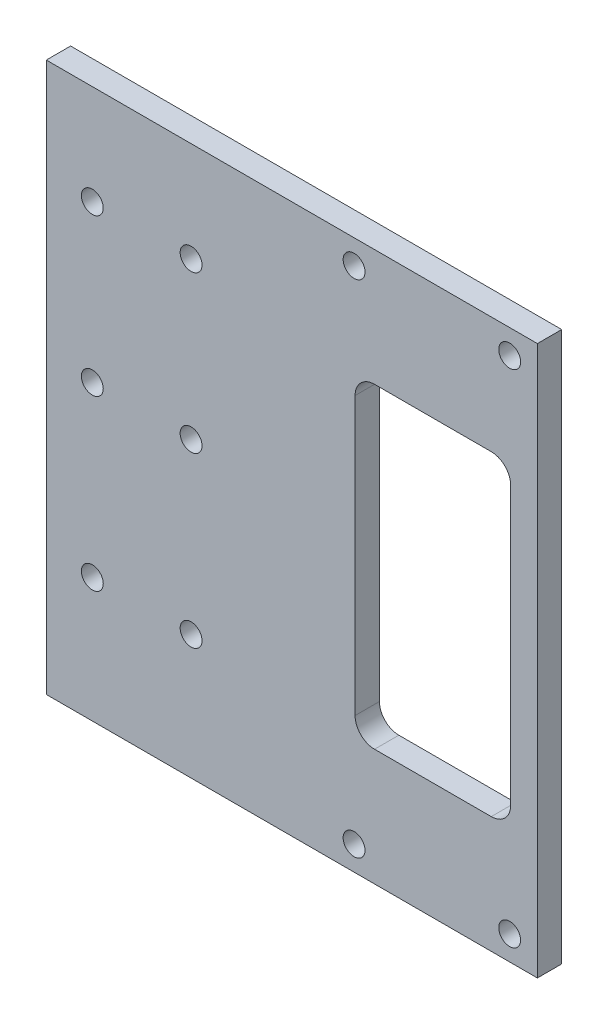
SolidWorks part; units mm, degrees
ref_plane "Plan de face" through (0, 0, 0) normal (0, 0, 1) x (1, 0, 0)
ref_plane "Plan de dessus" through (0, 0, 0) normal (0, 1, 0) x (1, 0, 0)
ref_plane "Plan de droite" through (0, 0, 0) normal (1, 0, 0) x (0, 0, -1)
sketch "Esquisse1" plane through (0, 0, 0) normal (0, 0, 1) x (1, 0, 0)
  line L1 (-50.5, -56.5) -> (50.5, -56.5)
  line L2 (-50.5, -56.5) -> (-50.5, 56.5)
  line L3 (-50.5, 56.5) -> (50.5, 56.5)
  line L4 (50.5, -56.5) -> (50.5, 56.5)
  line L5 (-50.5, -56.5) -> (50.5, 56.5) construction
  line L6 (-50.5, 56.5) -> (50.5, -56.5) construction
  point P0 (0, 0)
  dimension "D1" = 113
  dimension "D2" = 101
extrude "Boss.-Extru.1" add sketch "Esquisse1" along normal blind 5
hole_wizard "Dégagement M42" positions "Esquisse5" profile "Esquisse4" hole size "M4" standard "JIS" end condition through all
sketch "Esquisse5" plane through (0, 0, 5) normal (0, 0, 1) x (1, 0, 0)
  point P0 (-20.7231, -30.9129)
  point P2 (-20.7231, 3.8035)
  point P4 (-41.0358, 3.8035)
  point P6 (-41.0358, -30.9129)
  point P8 (-41.0358, 35.9838)
  point P10 (-20.7231, 35.9838)
sketch "Esquisse4" plane through (-20.7231, -30.9129, 5) normal (1, 0, 0) x (0, -1, 0)
  line L0 (0, 0) -> (0, 5)
  line L1 (0, 5) -> (2.25, 5)
  line L2 (2.25, 5) -> (2.25, 0)
  line L5 (2.25, 0) -> (0, 0)
  line L11 (0, -6.35) -> (0, 107.95) construction
  dimension "Diamètre du perçage jusqu'au prochain" = 4.5
  dimension "Profondeur du perçage jusqu'au prochain" = 5
hole_wizard "M4 Clearance Hole1" positions "Sketch2" profile "Sketch1" hole size "M4" standard "ANSI Metric" end condition through all
sketch "Sketch2" plane through (0, 0, 5) normal (0, 0, 1) x (1, 0, 0)
  point P0 (44.8, 51.5)
  point P3 (12.8, 51.5)
  point P6 (12.8, -51.5)
  point P9 (44.8, -51.5)
sketch "Sketch1" plane through (44.8, 51.5, 5) normal (1, 0, 0) x (0, -1, 0)
  line L0 (0, 0) -> (0, 5)
  line L1 (0, 5) -> (2.25, 5)
  line L2 (2.25, 5) -> (2.25, 0)
  line L5 (2.25, 0) -> (0, 0)
  line L11 (0, -6.35) -> (0, 107.95) construction
  dimension "Thru Hole Dia." = 4.5
  dimension "Thru Hole Depth" = 5
sketch "Sketch3" plane through (0, 0, 5) normal (0, 0, 1) x (1, 0, 0)
  line L0 (45.0083, 28.5) -> (45.0083, -28.5)
  line L1 (41.0083, 32.5) -> (17.0083, 32.5)
  line L2 (41.0083, -32.5) -> (17.0083, -32.5)
  line L3 (13.0083, 28.5) -> (13.0083, -28.5)
  line L4 (-50.5, -56.5) -> (50.5, -56.5) construction
  line L5 (50.5, 56.5) -> (-50.5, 56.5) construction
  arc A0 (13.0083, 28.5) -> (17.0083, 32.5) centre (17.0083, 28.5) cw
  arc A1 (13.0083, -28.5) -> (17.0083, -32.5) centre (17.0083, -28.5) ccw
  arc A2 (41.0083, -32.5) -> (45.0083, -28.5) centre (41.0083, -28.5) ccw
  arc A3 (41.0083, 32.5) -> (45.0083, 28.5) centre (41.0083, 28.5) cw
  dimension "D1" = 4
  dimension "D2" = 24
  dimension "D3" = 24
  dimension "D4" = 32
extrude "Cut-Extrude1" cut sketch "Sketch3" against normal through all
